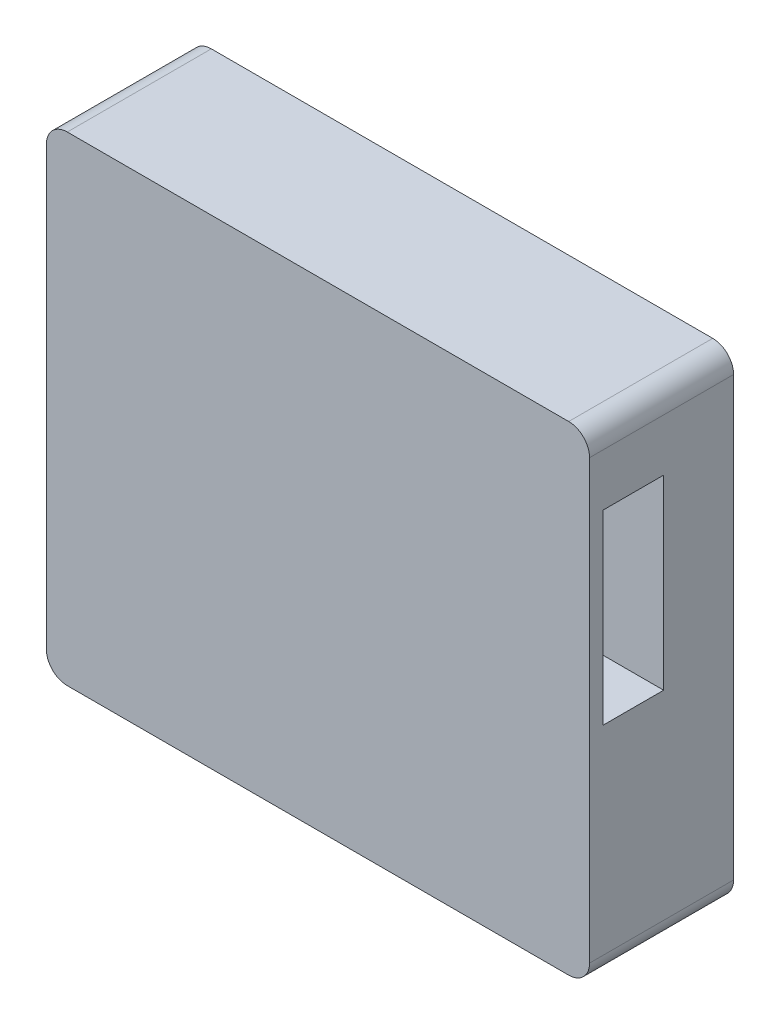
SolidWorks part; units mm, degrees
ref_plane "Front Plane" through (0, 0, 0) normal (0, 0, 1) x (1, 0, 0)
ref_plane "Top Plane" through (0, 0, 0) normal (0, 1, 0) x (1, 0, 0)
ref_plane "Right Plane" through (0, 0, 0) normal (1, 0, 0) x (0, 0, -1)
sketch "Sketch1" plane through (0, 0, 0) normal (0, 0, 1) x (1, 0, 0)
  line L4 (-14.4, -41.21) -> (84, -41.21)
  line L5 (86.1, -39.11) -> (86.1, 46.79)
  line L6 (84, 48.89) -> (-14.4, 48.89)
  line L7 (-16.5, 46.79) -> (-16.5, -39.11)
  line L8 (-14.4, -41.21) -> (84, -41.21)
  line L9 (86.1, -39.11) -> (86.1, 46.79)
  line L10 (84, 48.89) -> (-14.4, 48.89)
  line L11 (-16.5, 46.79) -> (-16.5, -39.11)
  arc A4 (84, -41.21) -> (86.1, -39.11) centre (84, -39.11) ccw
  arc A5 (86.1, 46.79) -> (84, 48.89) centre (84, 46.79) ccw
  arc A6 (-14.4, 48.89) -> (-16.5, 46.79) centre (-14.4, 46.79) ccw
  arc A7 (-16.5, -39.11) -> (-14.4, -41.21) centre (-14.4, -39.11) ccw
  arc A8 (84, -41.21) -> (86.1, -39.11) centre (84, -39.11) ccw
  arc A9 (86.1, 46.79) -> (84, 48.89) centre (84, 46.79) ccw
  arc A10 (-14.4, 48.89) -> (-16.5, 46.79) centre (-14.4, 46.79) ccw
  arc A11 (-16.5, -39.11) -> (-14.4, -41.21) centre (-14.4, -39.11) ccw
  dimension "D1" = 0
extrude "Boss-Extrude2" add sketch "Sketch1" against normal blind 2
sketch "Sketch3" plane through (0, 0, 0) normal (0, 0, 1) x (1, 0, 0)
  line L8 (-14.4, -43.21) -> (84, -43.21)
  line L9 (88.1, -39.11) -> (88.1, 46.79)
  line L10 (84, 50.89) -> (-14.4, 50.89)
  line L11 (-18.5, 46.79) -> (-18.5, -39.11)
  line L12 (-14.4, -43.21) -> (84, -43.21)
  line L13 (88.1, -39.11) -> (88.1, 46.79)
  line L14 (84, 50.89) -> (-14.4, 50.89)
  line L15 (-18.5, 46.79) -> (-18.5, -39.11)
  arc A8 (-18.5, -39.11) -> (-14.4, -43.21) centre (-14.4, -39.11) ccw
  arc A9 (84, -43.21) -> (88.1, -39.11) centre (84, -39.11) ccw
  arc A10 (88.1, 46.79) -> (84, 50.89) centre (84, 46.79) ccw
  arc A11 (-14.4, 50.89) -> (-18.5, 46.79) centre (-14.4, 46.79) ccw
  arc A12 (-18.5, -39.11) -> (-14.4, -43.21) centre (-14.4, -39.11) ccw
  arc A13 (84, -43.21) -> (88.1, -39.11) centre (84, -39.11) ccw
  arc A14 (88.1, 46.79) -> (84, 50.89) centre (84, 46.79) ccw
  arc A15 (-14.4, 50.89) -> (-18.5, 46.79) centre (-14.4, 46.79) ccw
  dimension "D1" = 2
extrude "Boss-Extrude3" add sketch "Sketch3" against normal up to surface (28.266 mm away)
sketch "Sketch4" plane through (0, -43.21, 0) normal (0, -1, 0) x (1, 0, 0)
  line L0 (72.33, -24.7898) -> (72.33, -28.2198) construction
  line L1 (72.33, -28.2198) -> (81.22, -28.2198) construction
  line L2 (81.22, -28.2198) -> (81.22, -24.7898) construction
  line L3 (81.22, -24.7898) -> (72.33, -24.7898) construction
  line L4 (68.12, -28.296) -> (69.827, -28.296) construction
  line L5 (69.827, -28.296) -> (69.827, -14.646) construction
  line L6 (69.827, -14.646) -> (68.12, -14.646) construction
  line L7 (66.12, -28.296) -> (68.12, -28.296) construction
  line L8 (68.12, -14.646) -> (66.12, -14.646) construction
  line L9 (57.38, -28.296) -> (66.12, -28.296) construction
  line L10 (66.12, -14.646) -> (57.38, -14.646) construction
  line L11 (55.38, -28.296) -> (57.38, -28.296) construction
  line L12 (57.38, -14.646) -> (55.38, -14.646) construction
  line L13 (53.673, -14.646) -> (53.673, -28.296) construction
  line L14 (53.673, -28.296) -> (55.38, -28.296) construction
  line L15 (55.38, -14.646) -> (53.673, -14.646) construction
  line L16 (37.375, -11.3798) -> (37.375, -28.2198) construction
  line L17 (37.375, -28.2198) -> (51.425, -28.2198) construction
  line L18 (51.425, -28.2198) -> (51.425, -11.3798) construction
  line L19 (51.425, -11.3798) -> (37.375, -11.3798) construction
  line L20 (20.375, -11.3798) -> (20.375, -28.2198) construction
  line L21 (20.375, -28.2198) -> (34.425, -28.2198) construction
  line L22 (34.425, -28.2198) -> (34.425, -11.3798) construction
  line L23 (34.425, -11.3798) -> (20.375, -11.3798) construction
  line L24 (-1.288, -21.4098) -> (-1.288, -28.2198) construction
  line L25 (-1.288, -28.2198) -> (16.408, -28.2198) construction
  line L26 (16.408, -28.2198) -> (16.408, -21.4098) construction
  line L27 (16.408, -21.4098) -> (-1.288, -21.4098) construction
  line L28 (-13.85, -17.296) -> (-13.85, -28.296) construction
  line L29 (-13.85, -28.296) -> (-4.55, -28.296) construction
  line L30 (-4.55, -28.296) -> (-4.55, -17.296) construction
  line L31 (-4.55, -17.296) -> (-13.85, -17.296) construction
  line L32 (72.33, -24.7898) -> (72.33, -28.2198)
  line L33 (72.33, -28.2198) -> (81.22, -28.2198)
  line L34 (81.22, -28.2198) -> (81.22, -24.7898)
  line L35 (81.22, -24.7898) -> (72.33, -24.7898)
  line L36 (68.12, -28.296) -> (69.827, -28.296)
  line L37 (69.827, -28.296) -> (69.827, -14.646)
  line L38 (69.827, -14.646) -> (68.12, -14.646)
  line L39 (66.12, -28.296) -> (68.12, -28.296)
  line L40 (68.12, -14.646) -> (66.12, -14.646)
  line L41 (57.38, -28.296) -> (66.12, -28.296)
  line L42 (66.12, -14.646) -> (57.38, -14.646)
  line L43 (55.38, -28.296) -> (57.38, -28.296)
  line L44 (57.38, -14.646) -> (55.38, -14.646)
  line L45 (53.673, -14.646) -> (53.673, -28.296)
  line L46 (53.673, -28.296) -> (55.38, -28.296)
  line L47 (55.38, -14.646) -> (53.673, -14.646)
  line L48 (37.375, -11.3798) -> (37.375, -28.2198)
  line L49 (37.375, -28.2198) -> (51.425, -28.2198)
  line L50 (51.425, -28.2198) -> (51.425, -11.3798)
  line L51 (51.425, -11.3798) -> (37.375, -11.3798)
  line L52 (20.375, -11.3798) -> (20.375, -28.2198)
  line L53 (20.375, -28.2198) -> (34.425, -28.2198)
  line L54 (34.425, -28.2198) -> (34.425, -11.3798)
  line L55 (34.425, -11.3798) -> (20.375, -11.3798)
  line L56 (-1.288, -21.4098) -> (-1.288, -28.2198)
  line L57 (-1.288, -28.2198) -> (16.408, -28.2198)
  line L58 (16.408, -28.2198) -> (16.408, -21.4098)
  line L59 (16.408, -21.4098) -> (-1.288, -21.4098)
  line L60 (-13.85, -17.296) -> (-13.85, -28.296)
  line L61 (-13.85, -28.296) -> (-4.55, -28.296)
  line L62 (-4.55, -28.296) -> (-4.55, -17.296)
  line L63 (-4.55, -17.296) -> (-13.85, -17.296)
sketch "Sketch5" plane through (88.1, 0, 0) normal (1, 0, 0) x (0, 0, -1)
  line L1 (2.6523, 36.5562) -> (14.5366, 36.5562)
  line L2 (2.6523, 36.5562) -> (2.6523, 0)
  line L3 (2.6523, 0) -> (14.5366, 0)
  line L4 (14.5366, 36.5562) -> (14.5366, 0)
extrude "Cut-Extrude3" cut sketch "Sketch5" against normal through all
sketch "Sketch7" plane through (0, -43.21, 0) normal (0, -1, 0) x (1, 0, 0)
  line L0 (72.33, -24.7898) -> (72.33, -28.2198) construction
  line L1 (72.33, -28.2198) -> (81.22, -28.2198) construction
  line L2 (81.22, -28.2198) -> (81.22, -24.7898) construction
  line L3 (81.22, -24.7898) -> (72.33, -24.7898) construction
  line L4 (68.12, -28.296) -> (69.827, -28.296) construction
  line L5 (69.827, -28.296) -> (69.827, -14.646) construction
  line L6 (69.827, -14.646) -> (68.12, -14.646) construction
  line L7 (66.12, -28.296) -> (68.12, -28.296) construction
  line L8 (68.12, -14.646) -> (66.12, -14.646) construction
  line L9 (57.38, -28.296) -> (66.12, -28.296) construction
  line L10 (66.12, -14.646) -> (57.38, -14.646) construction
  line L11 (55.38, -28.296) -> (57.38, -28.296) construction
  line L12 (57.38, -14.646) -> (55.38, -14.646) construction
  line L13 (53.673, -14.646) -> (53.673, -28.296) construction
  line L14 (53.673, -28.296) -> (55.38, -28.296) construction
  line L15 (55.38, -14.646) -> (53.673, -14.646) construction
  line L16 (37.375, -11.3798) -> (37.375, -28.2198) construction
  line L17 (37.375, -28.2198) -> (51.425, -28.2198) construction
  line L18 (51.425, -28.2198) -> (51.425, -11.3798) construction
  line L19 (51.425, -11.3798) -> (37.375, -11.3798) construction
  line L20 (20.375, -11.3798) -> (20.375, -28.2198) construction
  line L21 (20.375, -28.2198) -> (34.425, -28.2198) construction
  line L22 (34.425, -28.2198) -> (34.425, -11.3798) construction
  line L23 (34.425, -11.3798) -> (20.375, -11.3798) construction
  line L24 (-1.288, -21.4098) -> (-1.288, -28.2198) construction
  line L25 (-1.288, -28.2198) -> (16.408, -28.2198) construction
  line L26 (16.408, -28.2198) -> (16.408, -21.4098) construction
  line L27 (16.408, -21.4098) -> (-1.288, -21.4098) construction
  line L28 (-13.85, -17.296) -> (-13.85, -28.296) construction
  line L29 (-13.85, -28.296) -> (-4.55, -28.296) construction
  line L30 (-4.55, -28.296) -> (-4.55, -17.296) construction
  line L31 (-4.55, -17.296) -> (-13.85, -17.296) construction
  line L32 (72.33, -24.7898) -> (72.33, -28.2198)
  line L33 (72.33, -28.2198) -> (81.22, -28.2198)
  line L34 (81.22, -28.2198) -> (81.22, -24.7898)
  line L35 (81.22, -24.7898) -> (72.33, -24.7898)
  line L36 (68.12, -28.296) -> (69.827, -28.296)
  line L37 (69.827, -28.296) -> (69.827, -14.646)
  line L38 (69.827, -14.646) -> (68.12, -14.646)
  line L39 (66.12, -28.296) -> (68.12, -28.296)
  line L40 (68.12, -14.646) -> (66.12, -14.646)
  line L41 (57.38, -28.296) -> (66.12, -28.296)
  line L42 (66.12, -14.646) -> (57.38, -14.646)
  line L43 (55.38, -28.296) -> (57.38, -28.296)
  line L44 (57.38, -14.646) -> (55.38, -14.646)
  line L45 (53.673, -14.646) -> (53.673, -28.296)
  line L46 (53.673, -28.296) -> (55.38, -28.296)
  line L47 (55.38, -14.646) -> (53.673, -14.646)
  line L48 (37.375, -11.3798) -> (37.375, -28.2198)
  line L49 (37.375, -28.2198) -> (51.425, -28.2198)
  line L50 (51.425, -28.2198) -> (51.425, -11.3798)
  line L51 (51.425, -11.3798) -> (37.375, -11.3798)
  line L52 (20.375, -11.3798) -> (20.375, -28.2198)
  line L53 (20.375, -28.2198) -> (34.425, -28.2198)
  line L54 (34.425, -28.2198) -> (34.425, -11.3798)
  line L55 (34.425, -11.3798) -> (20.375, -11.3798)
  line L56 (-1.288, -21.4098) -> (-1.288, -28.2198)
  line L57 (-1.288, -28.2198) -> (16.408, -28.2198)
  line L58 (16.408, -28.2198) -> (16.408, -21.4098)
  line L59 (16.408, -21.4098) -> (-1.288, -21.4098)
  line L60 (-13.85, -17.296) -> (-13.85, -28.296)
  line L61 (-13.85, -28.296) -> (-4.55, -28.296)
  line L62 (-4.55, -28.296) -> (-4.55, -17.296)
  line L63 (-4.55, -17.296) -> (-13.85, -17.296)
extrude "Cut-Extrude4" cut sketch "Sketch7" against normal blind 32
